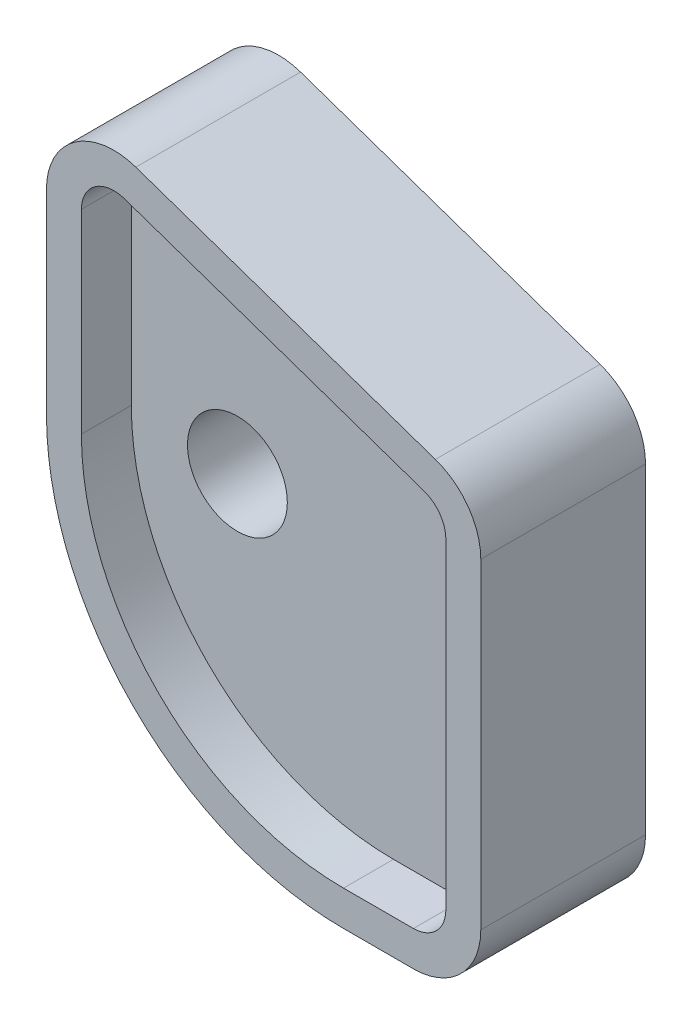
SolidWorks part; units mm, degrees
ref_plane "Front Plane" through (0, 0, 0) normal (0, 0, 1) x (1, 0, 0)
ref_plane "Top Plane" through (0, 0, 0) normal (0, 1, 0) x (1, 0, 0)
ref_plane "Right Plane" through (0, 0, 0) normal (1, 0, 0) x (0, 0, -1)
sketch "Sketch1" plane through (0, 0, 0) normal (0, 0, 1) x (1, 0, 0)
  line L8 (-47.825, -19.975) -> (-47.825, -23.875)
  line L9 (-41.875, -29.825) -> (-40.475, -29.825)
  line L10 (-39.125, -28.475) -> (-39.125, -22.0444)
  line L11 (-40.0348, -20.7681) -> (-46.0348, -18.6988)
  line L16 (-47.975, -19.975) -> (-47.975, -23.875)
  line L17 (-41.875, -29.975) -> (-40.475, -29.975)
  line L18 (-38.975, -28.475) -> (-38.975, -22.0444)
  line L19 (-39.9859, -20.6263) -> (-45.9859, -18.557)
  line L20 (-47.975, -19.975) -> (-47.975, -23.875) construction
  line L21 (-41.875, -29.975) -> (-40.475, -29.975) construction
  line L22 (-38.975, -28.475) -> (-38.975, -22.0444) construction
  line L23 (-39.9859, -20.6263) -> (-45.9859, -18.557) construction
  circle A9 centre (-45, -24) radius 1
  arc A10 (-47.825, -23.875) -> (-41.875, -29.825) centre (-41.875, -23.875) ccw
  arc A11 (-40.475, -29.825) -> (-39.125, -28.475) centre (-40.475, -28.475) ccw
  arc A16 (-45.9859, -18.557) -> (-47.975, -19.975) centre (-46.475, -19.975) ccw
  arc A17 (-47.975, -23.875) -> (-41.875, -29.975) centre (-41.875, -23.875) ccw
  arc A18 (-40.475, -29.975) -> (-38.975, -28.475) centre (-40.475, -28.475) ccw
  arc A19 (-38.975, -22.0444) -> (-39.9859, -20.6263) centre (-40.475, -22.0444) ccw
  arc A20 (-45.9859, -18.557) -> (-47.975, -19.975) centre (-46.475, -19.975) ccw construction
  arc A21 (-47.975, -23.875) -> (-41.875, -29.975) centre (-41.875, -23.875) ccw construction
  arc A22 (-40.475, -29.975) -> (-38.975, -28.475) centre (-40.475, -28.475) ccw construction
  arc A23 (-38.975, -22.0444) -> (-39.9859, -20.6263) centre (-40.475, -22.0444) ccw construction
  arc A24 (-39.125, -22.0444) -> (-40.0348, -20.7681) centre (-40.475, -22.0444) ccw
  arc A25 (-46.0348, -18.6988) -> (-47.825, -19.975) centre (-46.475, -19.975) ccw
  circle A27 centre (-45, -24) radius 0.8 construction
  circle A28 centre (-45, -24) radius 0.8 construction
  dimension "D6" = 2
  dimension "D1" = 0
  dimension "D2" = 0.15
extrude "Boss-Extrude1" add sketch "Sketch1" along normal blind 3.3
sketch "Sketch2" plane through (0, 0, 3.3) normal (0, 0, 1) x (1, 0, 0)
  line L0 (-47.125, -19.975) -> (-47.125, -23.875)
  line L1 (-41.875, -29.125) -> (-40.475, -29.125)
  line L2 (-39.825, -28.475) -> (-39.825, -22.0444)
  line L3 (-40.2631, -21.4299) -> (-46.2631, -19.3605)
  line L4 (-47.825, -19.975) -> (-47.825, -23.875)
  line L5 (-41.875, -29.825) -> (-40.475, -29.825)
  line L6 (-39.125, -28.475) -> (-39.125, -22.0444)
  line L7 (-40.0348, -20.7681) -> (-46.0348, -18.6988)
  line L8 (-47.825, -19.975) -> (-47.825, -23.875)
  line L9 (-41.875, -29.825) -> (-40.475, -29.825)
  line L10 (-39.125, -28.475) -> (-39.125, -22.0444)
  line L11 (-40.0348, -20.7681) -> (-46.0348, -18.6988)
  arc A0 (-47.125, -23.875) -> (-41.875, -29.125) centre (-41.875, -23.875) ccw
  arc A1 (-40.475, -29.125) -> (-39.825, -28.475) centre (-40.475, -28.475) ccw
  arc A2 (-39.825, -22.0444) -> (-40.2631, -21.4299) centre (-40.475, -22.0444) ccw
  arc A3 (-46.2631, -19.3605) -> (-47.125, -19.975) centre (-46.475, -19.975) ccw
  arc A4 (-46.0348, -18.6988) -> (-47.825, -19.975) centre (-46.475, -19.975) ccw
  arc A5 (-47.825, -23.875) -> (-41.875, -29.825) centre (-41.875, -23.875) ccw
  arc A6 (-40.475, -29.825) -> (-39.125, -28.475) centre (-40.475, -28.475) ccw
  arc A7 (-39.125, -22.0444) -> (-40.0348, -20.7681) centre (-40.475, -22.0444) ccw
  arc A8 (-46.0348, -18.6988) -> (-47.825, -19.975) centre (-46.475, -19.975) ccw
  arc A9 (-47.825, -23.875) -> (-41.875, -29.825) centre (-41.875, -23.875) ccw
  arc A10 (-40.475, -29.825) -> (-39.125, -28.475) centre (-40.475, -28.475) ccw
  arc A11 (-39.125, -22.0444) -> (-40.0348, -20.7681) centre (-40.475, -22.0444) ccw
  circle M17 centre (-45, -24) radius 1
  dimension "D1" = 0
  dimension "D2" = 0.7
extrude "Cut-Extrude1" cut sketch "Sketch2" against normal blind 1 contours L3 A3 L0 A0 L1 A1 L2 A2 M17
